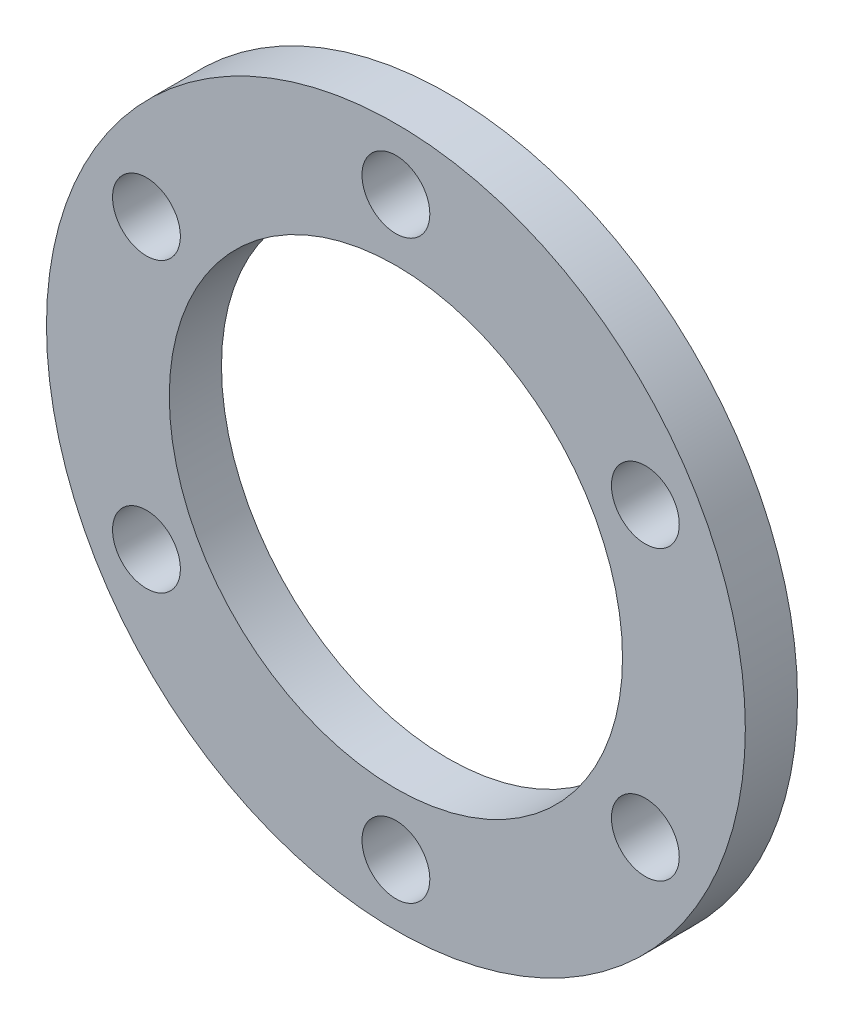
SolidWorks part; units mm, degrees
material "ABS"
ref_plane "Front Plane" through (0, 0, 0) normal (0, 0, 1) x (1, 0, 0)
ref_plane "Top Plane" through (0, 0, 0) normal (0, 1, 0) x (1, 0, 0)
ref_plane "Right Plane" through (0, 0, 0) normal (1, 0, 0) x (0, 0, -1)
sketch "Sketch1" plane through (0, 0, 0) normal (0, 0, 1) x (1, 0, 0)
  circle A0 centre (0, 0) radius 23.8252 construction
  circle A1 centre (0, 23.8252) radius 2.8067
  circle A2 centre (20.6332, 11.9126) radius 2.8067
  circle A3 centre (20.6332, -11.9126) radius 2.8067
  circle A4 centre (0, -23.8252) radius 2.8067
  circle A5 centre (-20.6332, -11.9126) radius 2.8067
  circle A6 centre (-20.6332, 11.9126) radius 2.8067
  circle A7 centre (0, 0) radius 28.9052
  circle A8 centre (0, 0) radius 18.7452
  point P17 (0, 0)
  dimension "D1" = 47.6504
  dimension "D2" = 5.6134
  dimension "D4" = 5.08
  dimension "D5" = 5.08
  dimension "D3" = 6
extrude "Boss-Extrude1" add sketch "Sketch1" along normal blind 4.318
